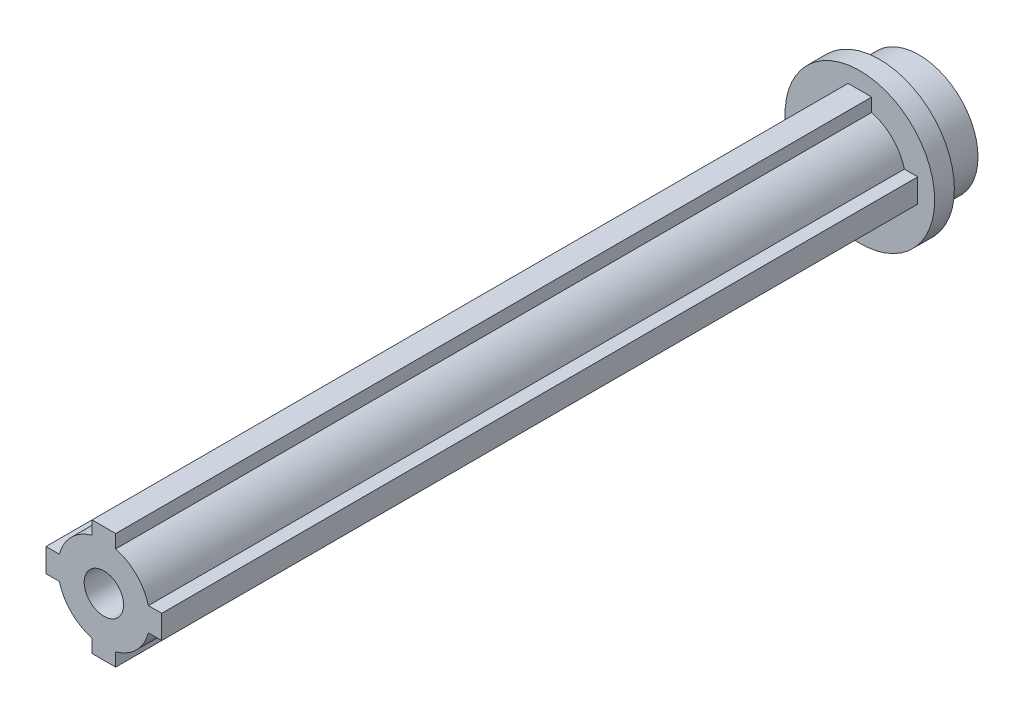
SolidWorks part; units mm, degrees
ref_plane "Front Plane" through (0, 0, 0) normal (0, 0, 1) x (1, 0, 0)
ref_plane "Top Plane" through (0, 0, 0) normal (0, 1, 0) x (1, 0, 0)
ref_plane "Right Plane" through (0, 0, 0) normal (1, 0, 0) x (0, 0, -1)
sketch "Sketch1" plane through (0, 0, 0) normal (0, 0, 1) x (1, 0, 0)
  circle A0 centre (0, 0) radius 7.5
  dimension "D1" = 15
extrude "Boss-Extrude1" add sketch "Sketch1" along normal blind 5
sketch "Sketch3" plane through (0, 0, 5) normal (0, 0, 1) x (1, 0, 0)
  circle A0 centre (0, 0) radius 9.5
  circle A1 centre (0, 0) radius 7.5 construction
  dimension "D1" = 2
extrude "Boss-Extrude2" add sketch "Sketch3" along normal blind 2.5
sketch "Sketch4" plane through (0, 0, 7.5) normal (0, 0, 1) x (1, 0, 0)
  line L0 (-1.5, 5.6528) -> (-1.5, 7.3485)
  line L1 (-1.5, 4.3485) -> (1.5, 4.3485) construction
  line L2 (-1.5, 4.3485) -> (-1.5, 7.3485) construction
  line L3 (-1.5, 7.3485) -> (1.5, 7.3485) construction
  line L4 (1.5, 4.3485) -> (1.5, 7.3485) construction
  line L5 (-1.5, 4.3485) -> (1.5, 7.3485) construction
  line L6 (-1.5, 7.3485) -> (1.5, 4.3485) construction
  line L7 (4.3485, -1.5) -> (7.3485, -1.5) construction
  line L8 (4.3485, -1.5) -> (4.3485, 1.5) construction
  line L9 (4.3485, 1.5) -> (7.3485, 1.5) construction
  line L10 (7.3485, -1.5) -> (7.3485, 1.5) construction
  line L11 (4.3485, -1.5) -> (7.3485, 1.5) construction
  line L12 (4.3485, 1.5) -> (7.3485, -1.5) construction
  line L13 (-1.5, -7.3485) -> (1.5, -7.3485) construction
  line L14 (-1.5, -7.3485) -> (-1.5, -4.3485) construction
  line L15 (-1.5, -4.3485) -> (1.5, -4.3485) construction
  line L16 (1.5, -7.3485) -> (1.5, -4.3485) construction
  line L17 (-1.5, -7.3485) -> (1.5, -4.3485) construction
  line L18 (-1.5, -4.3485) -> (1.5, -7.3485) construction
  line L19 (-7.3485, -1.5) -> (-4.3485, -1.5) construction
  line L20 (-7.3485, -1.5) -> (-7.3485, 1.5) construction
  line L21 (-7.3485, 1.5) -> (-4.3485, 1.5) construction
  line L22 (-4.3485, -1.5) -> (-4.3485, 1.5) construction
  line L23 (-7.3485, -1.5) -> (-4.3485, 1.5) construction
  line L24 (-7.3485, 1.5) -> (-4.3485, -1.5) construction
  line L25 (-1.5, 7.3485) -> (1.5, 7.3485)
  line L26 (1.5, 7.3485) -> (1.5, 5.6528)
  line L27 (5.6528, 1.5) -> (7.3485, 1.5)
  line L28 (7.3485, 1.5) -> (7.3485, -1.5)
  line L29 (7.3485, -1.5) -> (5.6528, -1.5)
  line L30 (1.5, -5.6528) -> (1.5, -7.3485)
  line L31 (1.5, -7.3485) -> (-1.5, -7.3485)
  line L32 (-1.5, -7.3485) -> (-1.5, -5.6528)
  line L33 (-5.6528, -1.5) -> (-7.3485, -1.5)
  line L34 (-7.3485, -1.5) -> (-7.3485, 1.5)
  line L35 (-7.3485, 1.5) -> (-5.6528, 1.5)
  circle A0 centre (0, 0) radius 7.5 construction
  arc A1 (-1.5, 5.6528) -> (-5.6528, 1.5) centre (0, 0) ccw
  arc A2 (5.6528, 1.5) -> (1.5, 5.6528) centre (0, 0) ccw
  arc A3 (1.5, -5.6528) -> (5.6528, -1.5) centre (0, 0) ccw
  arc A4 (-5.6528, -1.5) -> (-1.5, -5.6528) centre (0, 0) ccw
  point P4 (0, 5.8485)
  point P9 (5.8485, 0)
  point P14 (0, -5.8485)
  point P19 (-5.8485, 0)
  point P25 (1.5, 5.6528)
  point P26 (-1.5, 5.6528)
  point P27 (5.6528, 1.5)
  point P28 (5.6528, -1.5)
  point P29 (1.5, -5.6528)
  point P30 (-1.5, -5.6528)
  point P31 (-5.6528, -1.5)
  point P32 (-5.6528, 1.5)
  dimension "D1" = 15
  dimension "D2" = 3
extrude "Boss-Extrude3" add sketch "Sketch4" along normal blind 96
sketch "Sketch5" plane through (0, 0, 103.5) normal (0, 0, 1) x (1, 0, 0)
  circle A0 centre (0, 0) radius 2.5
  dimension "D1" = 5
extrude "Cut-Extrude1" cut sketch "Sketch5" against normal blind 5 contours A0
